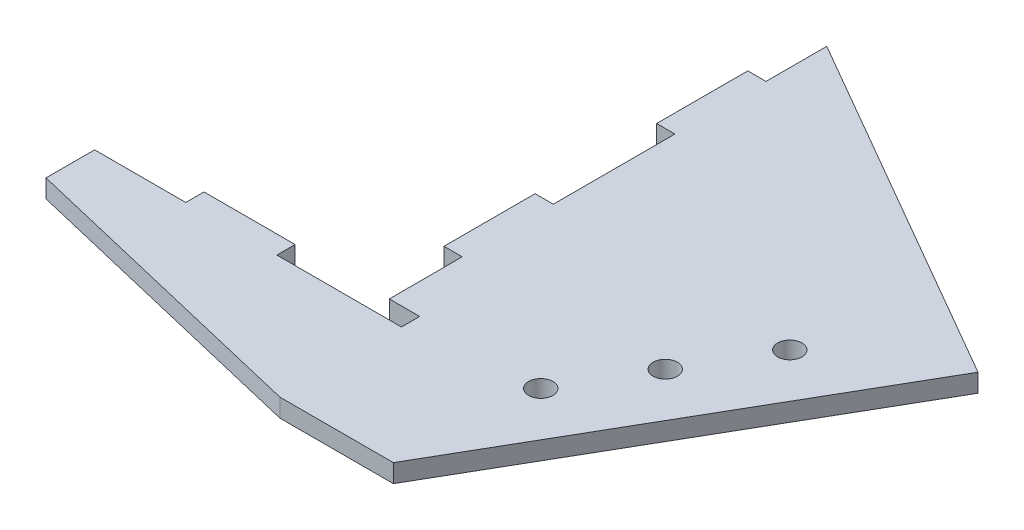
SolidWorks part; units mm, degrees
ref_plane "前视基准面" through (0, 0, 0) normal (0, 0, 1) x (1, 0, 0)
ref_plane "上视基准面" through (0, 0, 0) normal (0, 1, 0) x (1, 0, 0)
ref_plane "右视基准面" through (0, 0, 0) normal (1, 0, 0) x (0, 0, -1)
other "Configuration Table"
sketch "草图1" plane through (0, 0, 0) normal (0, 1, 0) x (1, 0, 0)
  line L0 (-7.5, -1.5) -> (-22.5, -1.5)
  line L1 (-7.5, 1.5) -> (7.5, 1.5)
  line L2 (-7.5, 1.5) -> (-7.5, -1.5)
  line L3 (-7.5, -1.5) -> (7.5, -1.5)
  line L4 (7.5, 1.5) -> (7.5, -1.5)
  line L5 (-7.5, 1.5) -> (7.5, -1.5) construction
  line L6 (-7.5, -1.5) -> (7.5, 1.5) construction
  line L7 (-22.5, -1.5) -> (28, -21.5)
  line L8 (28, -21.5) -> (28, -1.5)
  line L9 (28, -1.5) -> (7.5, -1.5)
  line L10 (28, -1.5) -> (28, 1.5)
  line L11 (28, 1.5) -> (23, 1.5)
  line L12 (23, 1.5) -> (23, 13.5)
  line L13 (23, 28.5) -> (23, 48.5)
  line L14 (23, 13.5) -> (20, 13.5)
  line L15 (23, 13.5) -> (23, 28.5)
  line L16 (23, 28.5) -> (20, 28.5)
  line L17 (20, 13.5) -> (20, 28.5)
  line L18 (23, 63.5) -> (23, 73.5)
  line L19 (23, 48.5) -> (20, 48.5)
  line L20 (23, 48.5) -> (23, 63.5)
  line L21 (23, 63.5) -> (20, 63.5)
  line L22 (20, 48.5) -> (20, 63.5)
  line L23 (23, 73.5) -> (81.8897, 39.5)
  line L24 (81.8897, 39.5) -> (46.6714, -21.5)
  line L25 (46.6714, -21.5) -> (28, -21.5)
  line L26 (-22.5, -1.5) -> (-22.5, -9.5)
  line L27 (-22.5, -9.5) -> (28, -21.5)
  point P0 (0, 0)
  dimension "D1" = 3
  dimension "D2" = 15
  dimension "D3" = 20.5
  dimension "D4" = 15
  dimension "D5" = 3
  dimension "D6" = 5
  dimension "D7" = 12
  dimension "D8" = 20
  dimension "D9" = 30
  dimension "D10" = 10
  dimension "D11" = 20
  dimension "D12" = 68
  dimension "D13" = 8
extrude "凸台-拉伸1" add sketch "草图1" along normal blind 3 contours L8 L9 L3 L0 L7 | L4 L1 L2 L3 | L17 L14 L15 L16 | L22 L19 L20 L21 | L25 L24 L23 L18 L20 L13 L15 L12 L11 L10 L8 | L26 L27 L7
sketch "草图2" plane through (0, 3, 0) normal (0, 1, 0) x (1, 0, 0)
  line L0 (73.2295, 44.5) -> (63.2295, 27.1795) construction
  line L1 (23, 73.5) -> (81.8897, 39.5) construction
  line L2 (81.8897, 39.5) -> (46.6714, -21.5) construction
  circle A0 centre (63.2295, 27.1795) radius 2
  circle A1 centre (55.7295, 14.1891) radius 2
  circle A2 centre (48.2295, 1.1987) radius 2
  dimension "D3" = 4
  dimension "D5" = 15
  dimension "D1" = 20
  dimension "D2" = 10
  dimension "D4" = 3
extrude "切除-拉伸1" cut sketch "草图2" against normal blind 3
